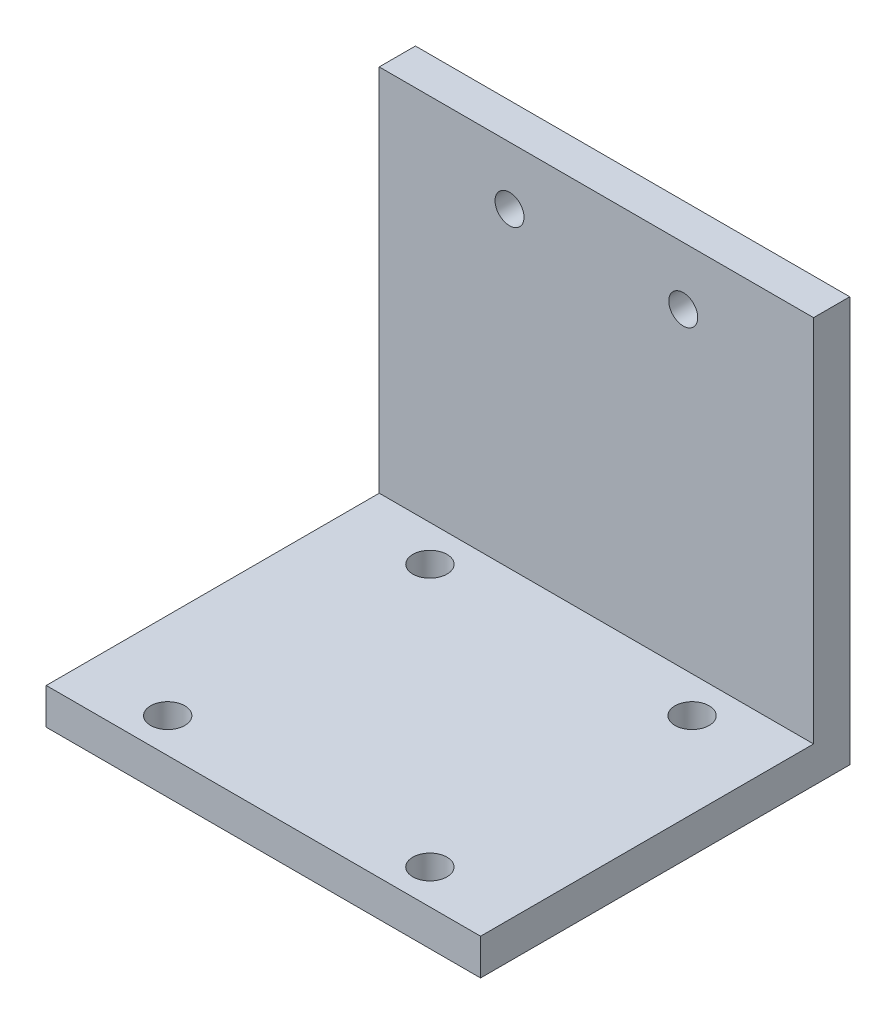
SolidWorks part; units mm, degrees
ref_plane "Front Plane" through (0, 0, 0) normal (0, 0, 1) x (1, 0, 0)
ref_plane "Top Plane" through (0, 0, 0) normal (0, 1, 0) x (1, 0, 0)
ref_plane "Right Plane" through (0, 0, 0) normal (1, 0, 0) x (0, 0, -1)
sketch "Sketch1" plane through (0, 0, 0) normal (0, 0, 1) x (1, 0, 0)
  line L1 (-10.5886, 11.4521) -> (27.5114, 11.4521)
  line L2 (-10.5886, 11.4521) -> (-10.5886, 1.2921)
  line L3 (-10.5886, 1.2921) -> (27.5114, 1.2921)
  line L4 (27.5114, 11.4521) -> (27.5114, 1.2921)
  circle A0 centre (16.0814, 6.3721) radius 1.27
  circle A1 centre (0.8414, 6.3721) radius 1.27
  point P8 (0, 0)
  point P9 (-30.2668, -16.827)
  dimension "D3" = 2.54
  dimension "D4" = 2.54
  dimension "D1" = 38.1
  dimension "D2" = 10.16
  dimension "D5" = 15.24
  dimension "D6" = 11.43
  dimension "D8" = 5.08
extrude "Boss-Extrude3" add sketch "Sketch1" against normal blind 3.175
sketch "Sketch7" plane through (0, 1.2921, 0) normal (0, -1, 0) x (1, 0, 0)
  line L1 (27.5114, 0) -> (-10.5886, 0)
  line L2 (27.5114, 0) -> (27.5114, -3.175)
  line L3 (27.5114, -3.175) -> (-10.5886, -3.175)
  line L4 (-10.5886, 0) -> (-10.5886, -3.175)
extrude "Boss-Extrude4" add sketch "Sketch7" along normal blind 25.4
sketch "Sketch8" plane through (0, 0, 0) normal (0, 0, 1) x (1, 0, 0)
  line L0 (-10.5886, 11.4521) -> (-10.5886, -24.1079) construction
  line L1 (27.5114, -24.1079) -> (-10.5886, -24.1079)
  line L2 (27.5114, -24.1079) -> (27.5114, -20.9329)
  line L3 (27.5114, -20.9329) -> (-10.5886, -20.9329)
  line L4 (-10.5886, -24.1079) -> (-10.5886, -20.9329)
  dimension "D1" = 3.175
extrude "Boss-Extrude6" add sketch "Sketch8" along normal blind 29.21
sketch "Sketch9" plane through (0, -24.1079, 0) normal (0, -1, 0) x (1, 0, 0)
  line L0 (-10.5886, -3.175) -> (27.5114, -3.175) construction
  line L1 (-2.9686, 26.175) -> (20.0314, 26.175)
  line L2 (-2.9686, 26.175) -> (-2.9686, 3.175)
  line L3 (-2.9686, 3.175) -> (20.0314, 3.175)
  line L4 (20.0314, 26.175) -> (20.0314, 3.175)
  line L7 (-10.5886, 29.21) -> (-10.5886, -3.175) construction
  line L8 (27.5114, -3.175) -> (27.5114, 29.21) construction
  dimension "D6" = 7.48
  dimension "D1" = 23
  dimension "D2" = 23
  dimension "D3" = 6.35
  dimension "D4" = 7.62
  dimension "D5" = 7.48
hole_wizard "#1 (0.228) Diameter Hole1" positions "3DSketch2" profile "Sketch10" hole size "#1" standard "ANSI Inch" end condition through all
sketch3d "3DSketch2"
  point P0 (-2.9686, -24.1079, 3.175)
  point P3 (20.0314, -24.1079, 3.175)
  point P6 (20.0314, -24.1079, 26.175)
  point P9 (-2.9686, -24.1079, 26.175)
sketch "Sketch10" plane through (-2.9686, -24.1079, 3.175) normal (1, 0, 0) x (0, 0, -1)
  line L0 (0, 0) -> (0, 35.56)
  line L1 (0, 35.56) -> (1.5, 35.56)
  line L2 (1.5, 35.56) -> (1.5, 0)
  line L5 (1.5, 0) -> (0, 0)
  line L11 (0, -6.35) -> (0, 107.95) construction
  dimension "Thru Hole Dia." = 3
  dimension "Thru Hole Depth" = 35.56
